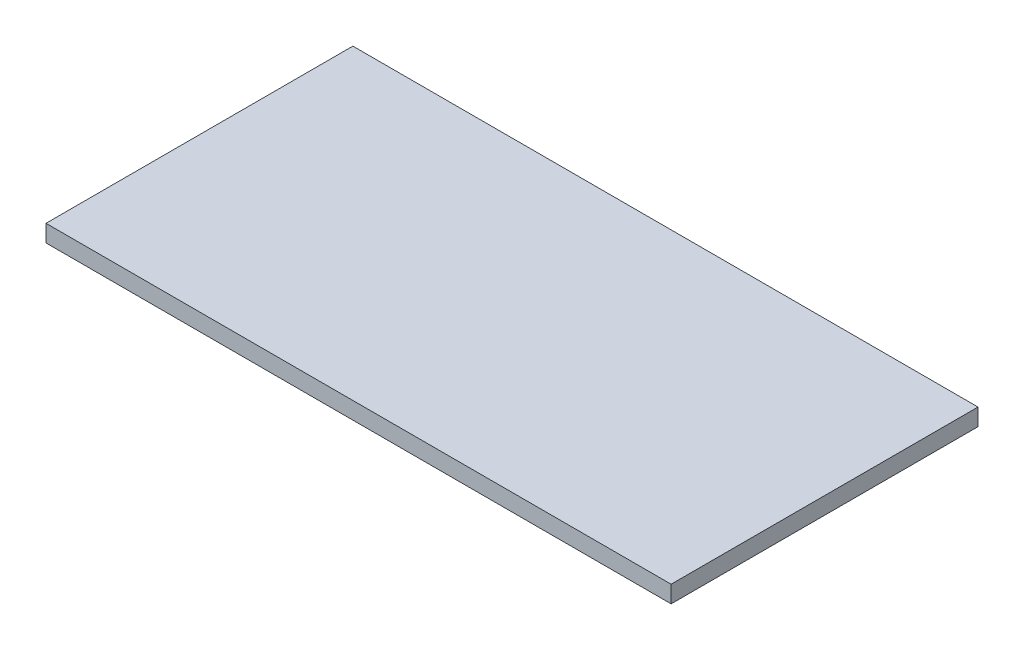
SolidWorks part; units mm, degrees
ref_plane "Plan de face" through (0, 0, 0) normal (0, 0, 1) x (1, 0, 0)
ref_plane "Plan de dessus" through (0, 0, 0) normal (0, 1, 0) x (1, 0, 0)
ref_plane "Plan de droite" through (0, 0, 0) normal (1, 0, 0) x (0, 0, -1)
sketch "Esquisse1" plane through (0, 0, 0) normal (0, 1, 0) x (1, 0, 0)
  line L1 (-54, 35.0217) -> (56, 35.0217)
  line L2 (-54, 35.0217) -> (-54, -18.9783)
  line L3 (-54, -18.9783) -> (56, -18.9783)
  line L4 (56, 35.0217) -> (56, -18.9783)
  dimension "D1" = 54
  dimension "D2" = 110
extrude "Boss.-Extru.1" add sketch "Esquisse1" along normal blind 3
